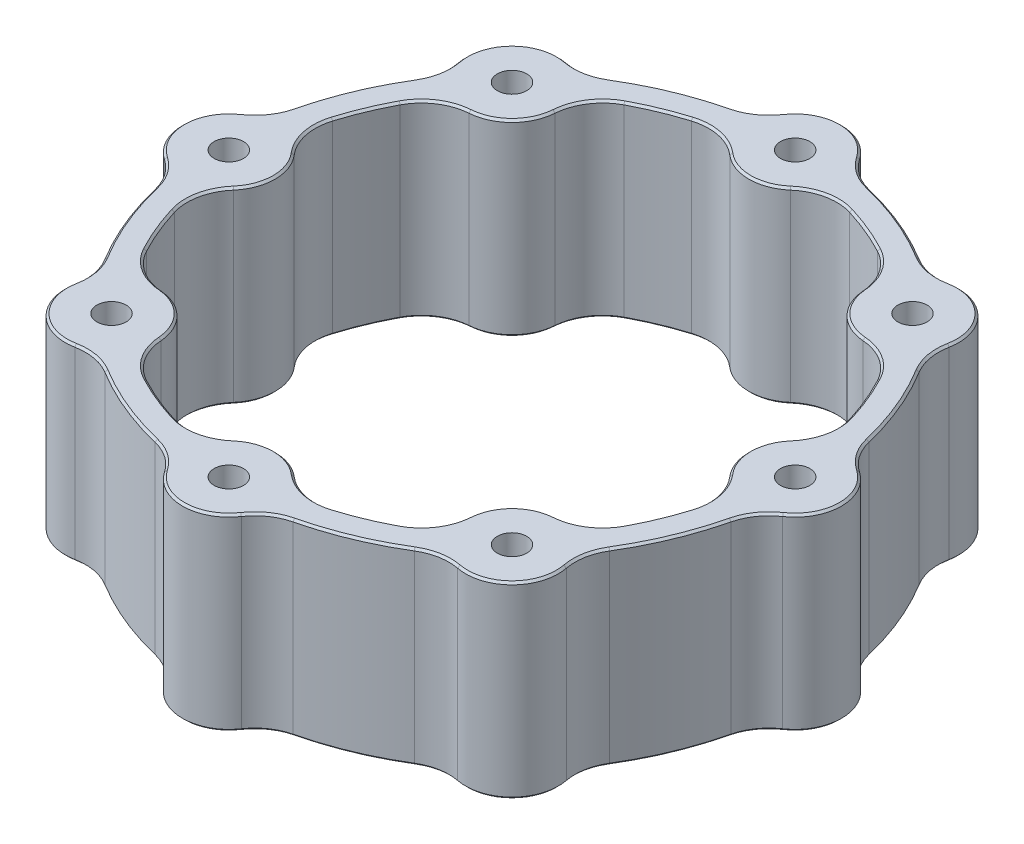
SolidWorks part; units mm, degrees
ref_plane "Front Plane" through (0, 0, 0) normal (0, 0, 1) x (1, 0, 0)
ref_plane "Top Plane" through (0, 0, 0) normal (0, 1, 0) x (1, 0, 0)
ref_plane "Right Plane" through (0, 0, 0) normal (1, 0, 0) x (0, 0, -1)
sketch "Sketch1" plane through (0, 0, 0) normal (0, 1, 0) x (1, 0, 0)
  circle A0 centre (0, 0) radius 55 construction
  circle A1 centre (0, 55) radius 9
  circle A2 centre (38.8909, 38.8909) radius 9
  circle A3 centre (55, 0) radius 9
  circle A4 centre (38.8909, -38.8909) radius 9
  circle A5 centre (0, -55) radius 9
  circle A6 centre (-38.8909, -38.8909) radius 9
  circle A7 centre (-55, 0) radius 9
  circle A8 centre (-38.8909, 38.8909) radius 9
  circle A9 centre (0, 0) radius 52.5
  circle A10 centre (0, 0) radius 57.5
  point P21 (0, 0)
  dimension "D1" = 110
  dimension "D2" = 18
  dimension "D4" = 115
  dimension "D5" = 105
  dimension "D3" = 8
extrude "Boss-Extrude1" add sketch "Sketch1" along normal blind 36.5 contours A8 A10 A7 A9 | A7 A9 | A7 A10 A9 | A10 A7 | A7 A10 A6 A9 | A6 A9 | A6 A10 A9 | A10 A6 | A6 A10 A5 A9 | A5 A9 | A5 A10 A9 | A5 A10 A4 A9 | A10 A5 | A4 A9 | A4 A10 A9 | A10 A4 | A3 A9 | A3 A10 A9 | A10 A3 | A4 A10 A3 A9 | A3 A10 A2 A9 | A2 A10 A9 | A10 A2 | A2 A9 | A10 A8 | A8 A10 A9 | A8 A9 | A1 A10 A8 A9 | A1 A10 A9 | A2 A10 A1 A9
sketch "Sketch4" plane through (0, 36.5, 0) normal (0, 1, 0) x (1, 0, 0)
  point P0 (0, 55)
  point P7 (38.8909, 38.8909)
  point P8 (55, 0)
  point P9 (38.8909, -38.8909)
  point P10 (0, -55)
  point P11 (-38.8909, -38.8909)
  point P12 (-55, 0)
  point P13 (-38.8909, 38.8909)
  dimension "D1" = 8
hole_wizard "M4 Clearance Hole1" positions "Sketch4" profile "Sketch3" hole size "M4" standard "DIN" end condition up to next
sketch "Sketch3" plane through (0, 36.5, -55) normal (1, 0, 0) x (0, 0, 1)
  line L0 (0, 0) -> (0, 36.5)
  line L1 (0, 36.5) -> (2.25, 36.5)
  line L2 (2.25, 36.5) -> (2.25, 0)
  line L5 (2.25, 0) -> (0, 0)
  line L11 (0, -6.35) -> (0, 107.95) construction
  dimension "Thru Hole Dia." = 4.5
  dimension "Thru Hole Depth" = 36.5
sketch "Sketch7" plane through (0, 36.5, 0) normal (0, 1, 0) x (1, 0, 0)
  point P0 (0, 55)
  point P7 (38.8909, 38.8909)
  point P8 (55, 0)
  point P9 (38.8909, -38.8909)
  point P10 (0, -55)
  point P11 (-38.8909, -38.8909)
  point P12 (-55, 0)
  point P13 (-38.8909, 38.8909)
  dimension "D1" = 8
hole_wizard "Ø5.7 (5.7) Diameter Hole1" positions "Sketch7" profile "Sketch8" hole size "Ø5.7" standard "DIN"
sketch "Sketch8" plane through (0, 36.5, -55) normal (1, 0, 0) x (0, 0, 1)
  line L0 (0, 0) -> (0, 11.7125)
  line L1 (0, 11.7125) -> (2.85, 10)
  line L2 (2.85, 10) -> (2.85, 0)
  line L5 (2.85, 0) -> (0, 0)
  line L10 (0, 11.7125) -> (-2.85, 10) construction
  line L11 (0, -6.35) -> (0, 107.95) construction
  dimension "Hole Dia." = 5.7
  dimension "Hole Depth" = 10
  dimension "Drill Angle" = 118
sketch "Sketch11" plane through (0, 0, 0) normal (0, -1, 0) x (-1, 0, 0)
  point P0 (0, 55)
  point P7 (38.8909, 38.8909)
  point P8 (55, 0)
  point P9 (38.8909, -38.8909)
  point P10 (0, -55)
  point P11 (-38.8909, -38.8909)
  point P12 (-55, 0)
  point P13 (-38.8909, 38.8909)
  dimension "D1" = 8
hole_wizard "Ø5.7 (5.7) Diameter Hole2" positions "Sketch11" profile "Sketch10" hole size "Ø5.7" standard "DIN"
sketch "Sketch10" plane through (0, 0, -55) normal (1, 0, 0) x (0, 0, -1)
  line L0 (0, 0) -> (0, 11.7125)
  line L1 (0, 11.7125) -> (2.85, 10)
  line L2 (2.85, 10) -> (2.85, 0)
  line L5 (2.85, 0) -> (0, 0)
  line L10 (0, 11.7125) -> (-2.85, 10) construction
  line L11 (0, -6.35) -> (0, 107.95) construction
  dimension "Hole Dia." = 5.7
  dimension "Hole Depth" = 10
  dimension "Drill Angle" = 118
fillet "Fillet2" radius 10 32 edges at (33.9457, 18.25, -46.4105) (46.4105, 18.25, -33.9457) (56.8205, 18.25, -8.814) (56.8205, 18.25, 8.814) (46.4105, 18.25, 33.9457) (33.9457, 18.25, 46.4105) (8.814, 18.25, 56.8205) (-8.814, 18.25, 56.8205) (-33.9457, 18.25, 46.4105) (-46.4105, 18.25, 33.9457) (-56.8205, 18.25, 8.814) (-56.8205, 18.25, -8.814) (-46.4105, 18.25, -33.9457) (-33.9457, 18.25, -46.4105) (8.814, 18.25, -56.8205) (-8.814, 18.25, -56.8205) (-30.689, 18.25, -42.5962) (-42.5962, 18.25, -30.689) (-51.8205, 18.25, -8.4196) (-51.8205, 18.25, 8.4196) (-42.5962, 18.25, 30.689) (-30.689, 18.25, 42.5962) (-8.4196, 18.25, 51.8205) (8.4196, 18.25, 51.8205) (30.689, 18.25, 42.5962) (42.5962, 18.25, 30.689) (51.8205, 18.25, 8.4196) (51.8205, 18.25, -8.4196) (42.5962, 18.25, -30.689) (30.689, 18.25, -42.5962) (8.4196, 18.25, -51.8205) (-8.4196, 18.25, -51.8205)
chamfer "Chamfer1" distance 0.4 angle 45 128 edges at (48.5037, 0, -20.0909) (42.9874, 0, -28.3205) (50.4223, 0, -10.3711) (32.5269, 0, -32.5269) (46, 0, 0) (28.3205, 0, -42.9874) (50.4223, 0, 10.3711) (20.0909, 0, -48.5037) (48.5037, 0, 20.0909) (10.3711, 0, -50.4223) (42.9874, 0, 28.3205) (0, 0, -46) (32.5269, 0, 32.5269) (-10.3711, 0, -50.4223) (28.3205, 0, 42.9874) (-20.0909, 0, -48.5037) (20.0909, 0, 48.5037) (-28.3205, 0, -42.9874) (10.3711, 0, 50.4223) (-32.5269, 0, -32.5269) (0, 0, 46) (-42.9874, 0, -28.3205) (-10.3711, 0, 50.4223) (-48.5037, 0, -20.0909) (-20.0909, 0, 48.5037) (-50.4223, 0, -10.3711) (-28.3205, 0, 42.9874) (-46, 0, 0) (-32.5269, 0, 32.5269) (-50.4223, 0, 10.3711) (-42.9874, 0, 28.3205) (-48.5037, 0, 20.0909) (-22.0043, 0, -53.1231) (-33.4971, 0, -47.7056) (-10.0469, 0, -57.419) (-45.2548, 0, -45.2548) (0, 0, -64) (-47.7056, 0, -33.4971) (10.0469, 0, -57.419) (-53.1231, 0, -22.0043) (22.0043, 0, -53.1231) (-57.419, 0, -10.0469) (33.4971, 0, -47.7056) (-64, 0, 0) (45.2548, 0, -45.2548) (-57.419, 0, 10.0469) (47.7056, 0, -33.4971) (-53.1231, 0, 22.0043) (53.1231, 0, -22.0043) (-47.7056, 0, 33.4971) (57.419, 0, -10.0469) (-45.2548, 0, 45.2548) (64, 0, 0) (-33.4971, 0, 47.7056) (57.419, 0, 10.0469) (-22.0043, 0, 53.1231) (53.1231, 0, 22.0043) (-10.0469, 0, 57.419) (47.7056, 0, 33.4971) (0, 0, 64) (45.2548, 0, 45.2548) (10.0469, 0, 57.419) (33.4971, 0, 47.7056) (22.0043, 0, 53.1231) (45.2548, 36.5, -45.2548) (33.4971, 36.5, -47.7056) (47.7056, 36.5, -33.4971) (22.0043, 36.5, -53.1231) (53.1231, 36.5, -22.0043) (10.0469, 36.5, -57.419) (57.419, 36.5, -10.0469) (0, 36.5, -64) (64, 36.5, 0) (-10.0469, 36.5, -57.419) (57.419, 36.5, 10.0469) (-22.0043, 36.5, -53.1231) (53.1231, 36.5, 22.0043) (-33.4971, 36.5, -47.7056) (47.7056, 36.5, 33.4971) (-45.2548, 36.5, -45.2548) (45.2548, 36.5, 45.2548) (-47.7056, 36.5, -33.4971) (33.4971, 36.5, 47.7056) (-53.1231, 36.5, -22.0043) (22.0043, 36.5, 53.1231) (-57.419, 36.5, -10.0469) (10.0469, 36.5, 57.419) (-64, 36.5, 0) (0, 36.5, 64) (-57.419, 36.5, 10.0469) (-10.0469, 36.5, 57.419) (-53.1231, 36.5, 22.0043) (-22.0043, 36.5, 53.1231) (-47.7056, 36.5, 33.4971) (-33.4971, 36.5, 47.7056) (-45.2548, 36.5, 45.2548) (20.0909, 36.5, -48.5037) (10.3711, 36.5, -50.4223) (28.3205, 36.5, -42.9874) (0, 36.5, -46) (32.5269, 36.5, -32.5269) (-10.3711, 36.5, -50.4223) (42.9874, 36.5, -28.3205) (-20.0909, 36.5, -48.5037) (48.5037, 36.5, -20.0909) (-28.3205, 36.5, -42.9874) (50.4223, 36.5, -10.3711) (-32.5269, 36.5, -32.5269) (46, 36.5, 0) (-42.9874, 36.5, -28.3205) (50.4223, 36.5, 10.3711) (-48.5037, 36.5, -20.0909) (48.5037, 36.5, 20.0909) (-50.4223, 36.5, -10.3711) (42.9874, 36.5, 28.3205) (-46, 36.5, 0) (32.5269, 36.5, 32.5269) (-50.4223, 36.5, 10.3711) (28.3205, 36.5, 42.9874) (-48.5037, 36.5, 20.0909) (20.0909, 36.5, 48.5037) (-42.9874, 36.5, 28.3205) (10.3711, 36.5, 50.4223) (-32.5269, 36.5, 32.5269) (0, 36.5, 46) (-28.3205, 36.5, 42.9874) (-10.3711, 36.5, 50.4223) (-20.0909, 36.5, 48.5037)
